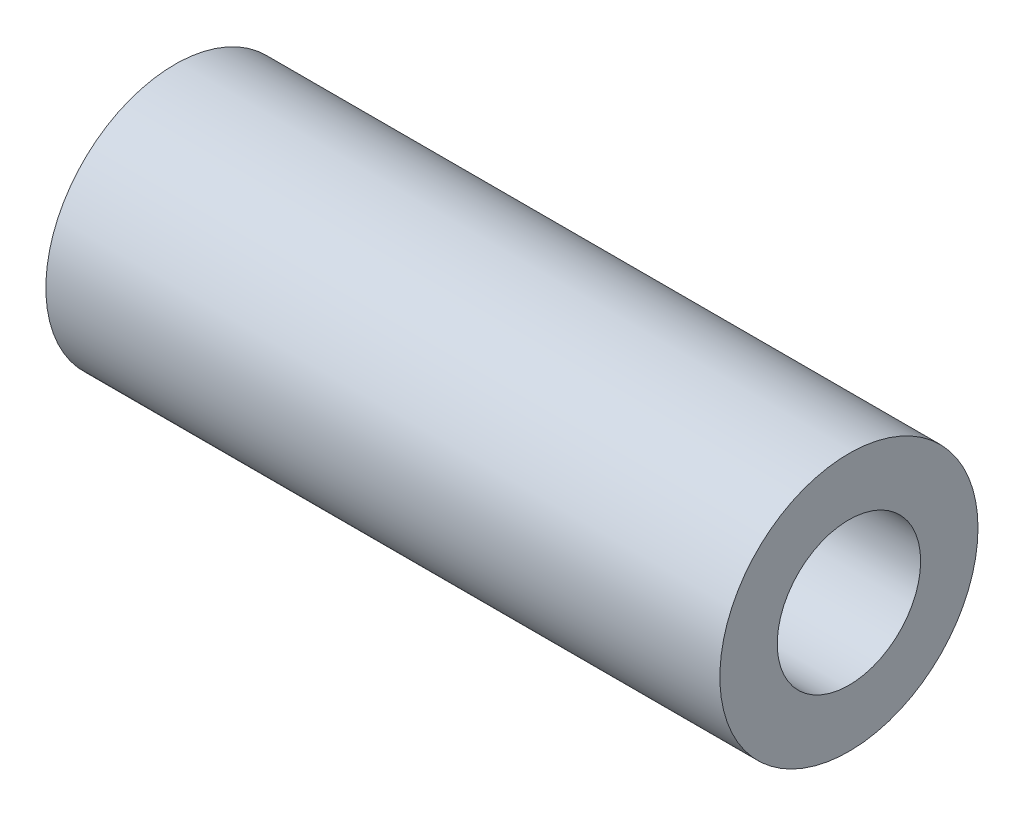
SolidWorks part; units mm, degrees
ref_plane "Front Plane" through (0, 0, 0) normal (0, 0, 1) x (1, 0, 0)
ref_plane "Top Plane" through (0, 0, 0) normal (0, 1, 0) x (1, 0, 0)
ref_plane "Right Plane" through (0, 0, 0) normal (1, 0, 0) x (0, 0, -1)
sketch "Sketch1" plane through (0, 0, 0) normal (1, 0, 0) x (0, 0, -1)
  circle A0 centre (0, 0) radius 2.5
  circle A1 centre (0, 0) radius 4.5
  dimension "D1" = 2
extrude "Boss-Extrude1" add sketch "Sketch1" along normal blind 23.5
